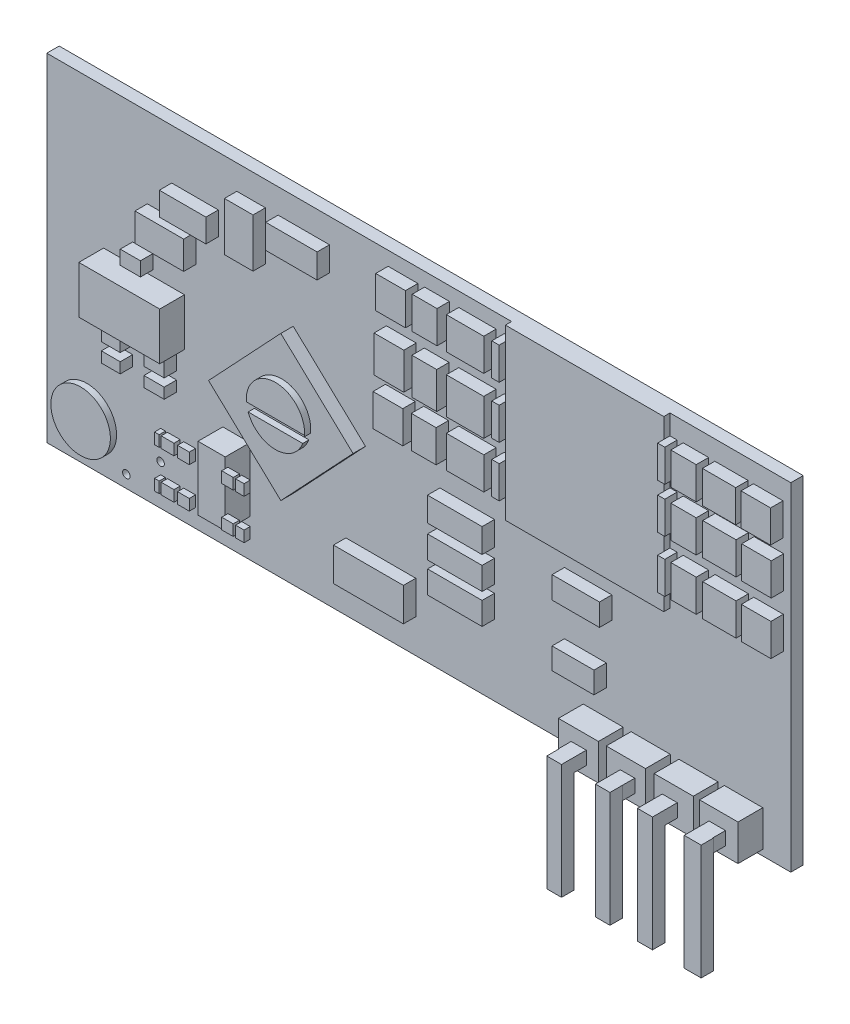
SolidWorks part; units mm, degrees
ref_plane "Front Plane" through (0, 0, 0) normal (0, 0, 1) x (1, 0, 0)
ref_plane "Top Plane" through (0, 0, 0) normal (0, 1, 0) x (1, 0, 0)
ref_plane "Right Plane" through (0, 0, 0) normal (1, 0, 0) x (0, 0, -1)
sketch "Sketch2" plane through (0, 0, 0) normal (0, 0, 1) x (1, 0, 0)
  line L1 (-9.0054, 3.5685) -> (20.9946, 3.5685)
  line L2 (-9.0054, 3.5685) -> (-9.0054, -10.0315)
  line L3 (-9.0054, -10.0315) -> (20.9946, -10.0315)
  line L4 (20.9946, 3.5685) -> (20.9946, -10.0315)
  dimension "D1" = 13.6
  dimension "D2" = 30
extrude "Boss-Extrude1" add sketch "Sketch2" along normal blind 0.5 contours L2 L1 L4 L3
sketch "Sketch3" plane through (0, 0, 0.5) normal (0, 0, 1) x (1, 0, 0)
  line L0 (-9.0054, 3.5685) -> (20.9946, 3.5685) construction
  line L1 (9.736, 3.5685) -> (16.1221, 3.5685)
  line L2 (9.736, 3.5685) -> (9.736, -3.2477)
  line L3 (9.736, -3.2477) -> (16.1221, -3.2477)
  line L4 (16.1221, 3.5685) -> (16.1221, -3.2477)
extrude "Boss-Extrude2" add sketch "Sketch3" along normal blind 0.25
sketch "Sketch4" plane through (0, 0, 0.5) normal (0, 0, 1) x (1, 0, 0)
  line L0 (16.1221, -3.2477) -> (16.1221, 3.5685) construction
  line L1 (16.1221, 2.7685) -> (16.4124, 2.7685)
  line L2 (16.1221, 2.7685) -> (16.1221, 1.4685)
  line L3 (16.1221, 1.4685) -> (16.4124, 1.4685)
  line L4 (16.4124, 2.7685) -> (16.4124, 1.4685)
  line L5 (16.1221, -3.2477) -> (16.1221, 3.5685) construction
  line L6 (16.6559, 2.7933) -> (17.6802, 2.7933)
  line L7 (16.6559, 2.7933) -> (16.6559, 1.4933)
  line L8 (16.6559, 1.4933) -> (17.6802, 1.4933)
  line L9 (17.6802, 2.7933) -> (17.6802, 1.4933)
  line L10 (17.9298, 2.787) -> (19.2737, 2.787)
  line L11 (17.9298, 2.787) -> (17.9298, 1.487)
  line L12 (17.9298, 1.487) -> (19.2737, 1.487)
  line L13 (19.2737, 2.787) -> (19.2737, 1.487)
  line L14 (19.4867, 2.7799) -> (20.6781, 2.7799)
  line L15 (19.4867, 2.7799) -> (19.4867, 1.4799)
  line L16 (19.4867, 1.4799) -> (20.6781, 1.4799)
  line L17 (20.6781, 2.7799) -> (20.6781, 1.4799)
  line L18 (16.1221, 0.9523) -> (16.4124, 0.9523)
  line L19 (16.1221, 0.9523) -> (16.1221, -0.3477)
  line L20 (16.1221, -0.3477) -> (16.4124, -0.3477)
  line L21 (16.4124, 0.9523) -> (16.4124, -0.3477)
  line L22 (9.736, 3.5685) -> (9.736, -3.2477) construction
  line L23 (17.9431, 0.9721) -> (19.287, 0.9721)
  line L24 (17.9431, 0.9721) -> (17.9431, -0.3279)
  line L25 (16.6559, 0.9361) -> (17.6802, 0.9361)
  line L26 (16.6559, 0.9361) -> (16.6559, -0.3639)
  line L27 (16.6559, -0.3639) -> (17.6802, -0.3639)
  line L28 (17.6802, 0.9361) -> (17.6802, -0.3639)
  line L29 (17.9431, -0.3279) -> (19.287, -0.3279)
  line L30 (19.287, 0.9721) -> (19.287, -0.3279)
  line L31 (19.5134, 0.9454) -> (20.7048, 0.9454)
  line L32 (19.5134, 0.9454) -> (19.5134, -0.3546)
  line L33 (19.5134, -0.3546) -> (20.7048, -0.3546)
  line L34 (20.7048, 0.9454) -> (20.7048, -0.3546)
  line L35 (16.1221, -1.1477) -> (16.4124, -1.1477)
  line L36 (16.1221, -1.1477) -> (16.1221, -2.4477)
  line L37 (16.1221, -2.4477) -> (16.4124, -2.4477)
  line L38 (16.4124, -1.1477) -> (16.4124, -2.4477)
  line L39 (16.6559, -1.1358) -> (17.6802, -1.1358)
  line L40 (16.6559, -1.1358) -> (16.6559, -2.4358)
  line L41 (16.6559, -2.4358) -> (17.6802, -2.4358)
  line L42 (17.6802, -1.1358) -> (17.6802, -2.4358)
  line L43 (17.9431, -1.1625) -> (19.287, -1.1625)
  line L44 (17.9431, -1.1625) -> (17.9431, -2.4625)
  line L45 (17.9431, -2.4625) -> (19.287, -2.4625)
  line L46 (19.287, -1.1625) -> (19.287, -2.4625)
  line L47 (19.5, -1.1759) -> (20.6914, -1.1759)
  line L48 (19.5, -1.1759) -> (19.5, -2.4759)
  line L49 (19.5, -2.4759) -> (20.6914, -2.4759)
  line L50 (20.6914, -1.1759) -> (20.6914, -2.4759)
  line L51 (9.736, -2.4477) -> (9.436, -2.4477)
  line L52 (9.736, -2.4477) -> (9.736, -1.1477)
  line L53 (9.736, -1.1477) -> (9.436, -1.1477)
  line L54 (9.436, -2.4477) -> (9.436, -1.1477)
  line L56 (9.736, -0.406) -> (9.436, -0.406)
  line L57 (9.736, -0.406) -> (9.736, 0.894)
  line L58 (9.736, 0.894) -> (9.436, 0.894)
  line L59 (9.436, -0.406) -> (9.436, 0.894)
  line L60 (9.736, 1.694) -> (9.436, 1.694)
  line L61 (9.736, 1.694) -> (9.736, 2.994)
  line L62 (9.736, 2.994) -> (9.436, 2.994)
  line L63 (9.436, 1.694) -> (9.436, 2.994)
  line L64 (9.1141, 2.994) -> (7.6057, 2.994)
  line L65 (9.1141, 2.994) -> (9.1141, 1.694)
  line L66 (9.1141, 1.694) -> (7.6057, 1.694)
  line L67 (7.6057, 2.994) -> (7.6057, 1.694)
  line L68 (7.6057, 0.894) -> (9.1141, 0.894)
  line L69 (7.6057, 0.894) -> (7.6057, -0.5749)
  line L70 (7.6057, -0.5749) -> (9.1141, -0.5749)
  line L71 (9.1141, 0.894) -> (9.1141, -0.5749)
  line L72 (9.1141, -1.1477) -> (7.6057, -1.1477)
  line L73 (9.1141, -1.1477) -> (9.1141, -2.4477)
  line L74 (9.1141, -2.4477) -> (7.6057, -2.4477)
  line L75 (7.6057, -1.1477) -> (7.6057, -2.4477)
  line L76 (7.2285, 3.0173) -> (6.2285, 3.0173)
  line L77 (7.2285, 3.0173) -> (7.2285, 1.7173)
  line L78 (7.2285, 1.7173) -> (6.2285, 1.7173)
  line L79 (6.2285, 3.0173) -> (6.2285, 1.7173)
  line L80 (7.2169, 0.8823) -> (6.2169, 0.8823)
  line L81 (7.2169, 0.8823) -> (7.2169, -0.5865)
  line L82 (7.2169, -0.5865) -> (6.2169, -0.5865)
  line L83 (6.2169, 0.8823) -> (6.2169, -0.5865)
  line L84 (7.1936, -1.1593) -> (6.1936, -1.1593)
  line L85 (7.1936, -1.1593) -> (7.1936, -2.4593)
  line L86 (7.1936, -2.4593) -> (6.1936, -2.4593)
  line L87 (6.1936, -1.1593) -> (6.1936, -2.4593)
  line L88 (5.9576, 3.0078) -> (4.7576, 3.0078)
  line L89 (5.9576, 3.0078) -> (5.9576, 1.7078)
  line L90 (5.9576, 1.7078) -> (4.7576, 1.7078)
  line L91 (4.7576, 3.0078) -> (4.7576, 1.7078)
  line L92 (5.8903, 0.8951) -> (4.6903, 0.8951)
  line L93 (5.8903, 0.8951) -> (5.8903, -0.5737)
  line L94 (5.8903, -0.5737) -> (4.6903, -0.5737)
  line L95 (4.6903, 0.8951) -> (4.6903, -0.5737)
  line L96 (5.8494, -1.1678) -> (4.6494, -1.1678)
  line L97 (5.8494, -1.1678) -> (5.8494, -2.4678)
  line L98 (5.8494, -2.4678) -> (4.6494, -2.4678)
  line L99 (4.6494, -1.1678) -> (4.6494, -2.4678)
  dimension "D1" = 1.3
  dimension "D2" = 1.3
  dimension "D3" = 1.3
  dimension "D4" = 1.3
  dimension "D5" = 1.3
  dimension "D6" = 1.3
  dimension "D7" = 1.3
  dimension "D8" = 1.3
  dimension "D9" = 1.3
  dimension "D10" = 1.3
  dimension "D11" = 1.3
  dimension "D12" = 1.3
  dimension "D13" = 0.8
  dimension "D14" = 0.8
  dimension "D15" = 0.8
  dimension "D16" = 1.3
  dimension "D17" = 1.3
  dimension "D18" = 1.3
  dimension "D19" = 0.8
  dimension "D20" = 0.8
  dimension "D21" = 0.8
  dimension "D22" = 0.2903
  dimension "D23" = 0.3
  dimension "D24" = 0.3
  dimension "D25" = 0.3
  dimension "D26" = 1.0243
  dimension "D27" = 1
  dimension "D28" = 1
  dimension "D29" = 1
  dimension "D30" = 1.4688
  dimension "D31" = 1.1914
  dimension "D32" = 1.2
  dimension "D33" = 1.2
  dimension "D34" = 1.2
extrude "Boss-Extrude8" add sketch "Sketch4" along normal blind 0.5
sketch "Sketch5" plane through (0, 0, 0.5) normal (0, 0, 1) x (1, 0, 0)
  line L1 (6.8465, -3.6881) -> (9.0462, -3.6881)
  line L2 (6.8465, -3.6881) -> (6.8465, -4.6657)
  line L3 (6.8465, -4.6657) -> (9.0462, -4.6657)
  line L4 (9.0462, -3.6881) -> (9.0462, -4.6657)
  line L5 (6.8465, -5.0435) -> (9.0462, -5.0435)
  line L6 (6.8465, -5.0435) -> (6.8465, -5.9544)
  line L7 (6.8465, -5.9544) -> (9.0462, -5.9544)
  line L8 (9.0462, -5.0435) -> (9.0462, -5.9544)
  line L9 (6.8465, -6.2655) -> (9.0462, -6.2655)
  line L10 (6.8465, -6.2655) -> (6.8465, -7.1765)
  line L11 (6.8465, -7.1765) -> (9.0462, -7.1765)
  line L12 (9.0462, -6.2655) -> (9.0462, -7.1765)
  line L13 (11.868, -3.9547) -> (13.7789, -3.9547)
  line L14 (11.868, -3.9547) -> (11.868, -4.8435)
  line L15 (11.868, -4.8435) -> (13.7789, -4.8435)
  line L16 (13.7789, -3.9547) -> (13.7789, -4.8435)
  line L17 (11.868, -6.4433) -> (13.5567, -6.4433)
  line L18 (11.868, -6.4433) -> (11.868, -7.3098)
  line L19 (11.868, -7.3098) -> (13.5567, -7.3098)
  line L20 (13.5567, -6.4433) -> (13.5567, -7.3098)
extrude "Boss-Extrude9" add sketch "Sketch5" along normal blind 0.5
sketch "Sketch6" plane through (0, 0, 0.5) normal (0, 0, 1) x (1, 0, 0)
  line L1 (12.625, -8.3439) -> (14.2373, -8.3439)
  line L2 (12.625, -8.3439) -> (12.625, -9.7981)
  line L3 (12.625, -9.7981) -> (14.2373, -9.7981)
  line L4 (14.2373, -8.3439) -> (14.2373, -9.7981)
  line L5 (14.5534, -8.3439) -> (16.1341, -8.3439)
  line L6 (14.5534, -8.3439) -> (14.5534, -9.7981)
  line L7 (14.5534, -9.7981) -> (16.1341, -9.7981)
  line L8 (16.1341, -8.3439) -> (16.1341, -9.7981)
  line L9 (16.4818, -8.3439) -> (18.0625, -8.3439)
  line L10 (16.4818, -8.3439) -> (16.4818, -9.7981)
  line L11 (16.4818, -9.7981) -> (18.0625, -9.7981)
  line L12 (18.0625, -8.3439) -> (18.0625, -9.7981)
  line L13 (18.3154, -8.3439) -> (19.8645, -8.3439)
  line L14 (18.3154, -8.3439) -> (18.3154, -9.7981)
  line L15 (18.3154, -9.7981) -> (19.8645, -9.7981)
  line L16 (19.8645, -8.3439) -> (19.8645, -9.7981)
extrude "Boss-Extrude11" add sketch "Sketch6" along normal blind 1
sketch "Sketch7" plane through (0, 0, 1.5) normal (0, 0, 1) x (1, 0, 0)
  line L1 (13.1379, -8.8933) -> (13.7485, -8.8933)
  line L2 (13.1379, -8.8933) -> (13.1379, -9.4308)
  line L3 (13.1379, -9.4308) -> (13.7485, -9.4308)
  line L4 (13.7485, -8.8933) -> (13.7485, -9.4308)
  line L5 (15.1169, -8.8933) -> (15.7036, -8.8933)
  line L6 (15.1169, -8.8933) -> (15.1169, -9.4308)
  line L7 (15.1169, -9.4308) -> (15.7036, -9.4308)
  line L8 (15.7036, -8.8933) -> (15.7036, -9.4308)
  line L9 (16.8122, -8.8933) -> (17.4173, -8.8933)
  line L10 (16.8122, -8.8933) -> (16.8122, -9.4308)
  line L11 (16.8122, -9.4308) -> (17.4173, -9.4308)
  line L12 (17.4173, -8.8933) -> (17.4173, -9.4308)
  line L13 (18.6964, -8.8933) -> (19.3604, -8.8933)
  line L14 (18.6964, -8.8933) -> (18.6964, -9.4308)
  line L15 (18.6964, -9.4308) -> (19.3604, -9.4308)
  line L16 (19.3604, -8.8933) -> (19.3604, -9.4308)
extrude "Boss-Extrude12" add sketch "Sketch7" along normal blind 0.5
sketch "Sketch8" plane through (0, 0, 2) normal (0, 0, 1) x (1, 0, 0)
  line L0 (13.7485, -8.8933) -> (13.1379, -8.8933) construction
  line L1 (13.1548, -8.8933) -> (13.7485, -8.8933)
  line L2 (13.1548, -8.8933) -> (13.1548, -13.5335)
  line L3 (13.1548, -13.5335) -> (13.7485, -13.5335)
  line L4 (13.7485, -8.8933) -> (13.7485, -13.5335)
  line L5 (18.6964, -8.8933) -> (18.6964, -9.4308) construction
  line L6 (15.1169, -8.8933) -> (15.7029, -8.8933)
  line L7 (15.1169, -8.8933) -> (15.1169, -13.5335)
  line L8 (15.1169, -13.5335) -> (15.7029, -13.5335)
  line L9 (15.7029, -8.8933) -> (15.7029, -13.5335)
  line L10 (16.8122, -8.8933) -> (17.4173, -8.8933)
  line L11 (16.8122, -8.8933) -> (16.8122, -13.5335)
  line L12 (16.8122, -13.5335) -> (17.4173, -13.5335)
  line L13 (17.4173, -8.8933) -> (17.4173, -13.5335)
  line L14 (18.6964, -8.8933) -> (19.3797, -8.8933)
  line L15 (18.6964, -8.8933) -> (18.6964, -13.5335)
  line L16 (18.6964, -13.5335) -> (19.3797, -13.5335)
  line L17 (19.3797, -8.8933) -> (19.3797, -13.5335)
extrude "Boss-Extrude13" add sketch "Sketch8" along normal blind 0.5
sketch "Sketch9" plane through (0, 0, 0.5) normal (0, 0, 1) x (1, 0, 0)
  line L0 (0.9308, -0.9992) -> (-1.9824, -4.1004)
  line L1 (0.9308, -0.9992) -> (3.8441, -3.7359)
  line L2 (-1.9824, -4.1004) -> (0.9308, -6.8371)
  line L3 (3.8441, -3.7359) -> (0.9308, -6.8371)
extrude "Boss-Extrude14" add sketch "Sketch9" along normal blind 0.5
sketch "Sketch10" plane through (0, 0, 1) normal (0, 0, 1) x (1, 0, 0)
  circle A0 centre (0.9631, -3.7408) radius 1.174
extrude "Boss-Extrude16" add sketch "Sketch10" along normal blind 0.25
sketch "Sketch12" plane through (0, 0, 1.25) normal (0, 0, 1) x (1, 0, 0)
  line L1 (-0.2073, -3.8339) -> (2.128, -3.8339)
  line L2 (-0.2073, -3.8339) -> (-0.2073, -4.1503)
  line L3 (-0.2073, -4.1503) -> (2.128, -4.1503)
  line L4 (2.128, -3.8339) -> (2.128, -4.1503)
  circle A0 centre (0.9631, -3.7408) radius 1.174 construction
extrude "Cut-Extrude6" cut sketch "Sketch12" against normal blind 0.25 contours L2 L1 L4 L3
sketch "Sketch13" plane through (0, 0, 0.5) normal (0, 0, 1) x (1, 0, 0)
  circle A0 centre (-7.3905, -8.353) radius 1.2
  dimension "D1" = 2.4
extrude "Boss-Extrude17" add sketch "Sketch13" along normal blind 0.25
sketch "Sketch14" plane through (0, 0, 0.5) normal (0, 0, 1) x (1, 0, 0)
  line L1 (-1.9075, -5.934) -> (-0.8109, -5.934)
  line L2 (-1.9075, -5.934) -> (-1.9075, -8.5143)
  line L3 (-1.9075, -8.5143) -> (-0.8109, -8.5143)
  line L4 (-0.8109, -5.934) -> (-0.8109, -8.5143)
extrude "Boss-Extrude19" add sketch "Sketch14" along normal blind 1
sketch "Sketch15" plane through (0, 0, 1.5) normal (0, 0, 1) x (1, 0, 0)
  line L1 (-2.0102, -6.2379) -> (-2.4824, -6.2379)
  line L2 (-2.0102, -6.2379) -> (-2.0102, -6.6811)
  line L3 (-2.0102, -6.6811) -> (-2.4824, -6.6811)
  line L4 (-2.4824, -6.2379) -> (-2.4824, -6.6811)
  line L5 (-2.6277, -6.2379) -> (-3.1435, -6.2379)
  line L6 (-2.6277, -6.2379) -> (-2.6277, -6.6811)
  line L7 (-2.6277, -6.6811) -> (-3.1435, -6.6811)
  line L8 (-3.1435, -6.2379) -> (-3.1435, -6.6811)
  line L9 (-3.4123, -6.2379) -> (-3.2234, -6.2379)
  line L10 (-3.4123, -6.2379) -> (-3.4123, -6.6811)
  line L11 (-3.4123, -6.6811) -> (-3.2234, -6.6811)
  line L12 (-3.2234, -6.2379) -> (-3.2234, -6.6811)
  line L13 (-2.0102, -8.301) -> (-2.4824, -8.301)
  line L14 (-2.0102, -8.301) -> (-2.0102, -7.8579)
  line L15 (-2.0102, -7.8579) -> (-2.4824, -7.8579)
  line L16 (-2.4824, -8.301) -> (-2.4824, -7.8579)
  line L17 (-2.6277, -7.8579) -> (-3.1435, -7.8579)
  line L18 (-2.6277, -7.8579) -> (-2.6277, -8.301)
  line L19 (-2.6277, -8.301) -> (-3.1435, -8.301)
  line L20 (-3.1435, -7.8579) -> (-3.1435, -8.301)
  line L21 (-3.2234, -7.8579) -> (-3.4123, -7.8579)
  line L22 (-3.2234, -7.8579) -> (-3.2234, -8.301)
  line L23 (-3.2234, -8.301) -> (-3.4123, -8.301)
  line L24 (-3.4123, -7.8579) -> (-3.4123, -8.301)
  line L25 (-0.7026, -6.2379) -> (-0.2377, -6.2379)
  line L26 (-0.7026, -6.2379) -> (-0.7026, -6.6811)
  line L27 (-0.7026, -6.6811) -> (-0.2377, -6.6811)
  line L28 (-0.2377, -6.2379) -> (-0.2377, -6.6811)
  line L29 (-0.1433, -6.2379) -> (0.1982, -6.2379)
  line L30 (-0.1433, -6.2379) -> (-0.1433, -6.6811)
  line L31 (-0.1433, -6.6811) -> (0.1982, -6.6811)
  line L32 (0.1982, -6.2379) -> (0.1982, -6.6811)
  line L33 (-0.7026, -7.8579) -> (-0.2377, -7.8579)
  line L34 (-0.7026, -7.8579) -> (-0.7026, -8.301)
  line L35 (-0.7026, -8.301) -> (-0.2377, -8.301)
  line L36 (-0.2377, -7.8579) -> (-0.2377, -8.301)
  line L37 (-0.1433, -7.8579) -> (0.1982, -7.8579)
  line L38 (-0.1433, -7.8579) -> (-0.1433, -8.301)
  line L39 (-0.1433, -8.301) -> (0.1982, -8.301)
  line L40 (0.1982, -7.8579) -> (0.1982, -8.301)
extrude "Boss-Extrude20" add sketch "Sketch15" along normal blind 0.25 separate body
sketch "Sketch16" plane through (0, 0, 0.5) normal (0, 0, 1) x (1, 0, 0)
  circle A0 centre (-5.7988, -9.5294) radius 0.15
  circle A1 centre (-4.4159, -8.4091) radius 0.15
  dimension "D1" = 0.3
  dimension "D2" = 0.3
extrude "Cut-Extrude7" cut sketch "Sketch16" against normal blind 4.25
sketch "Sketch17" plane through (0, 0, 0.5) normal (0, 0, 1) x (1, 0, 0)
  line L1 (-6.2949, -1.9058) -> (-2.8154, -1.9058)
  line L2 (-6.2949, -1.9058) -> (-6.2949, -3.5495)
  line L3 (-6.2949, -3.5495) -> (-2.8154, -3.5495)
  line L4 (-2.8154, -1.9058) -> (-2.8154, -3.5495)
  line L5 (-4.9501, -0.7958) -> (-2.9862, -0.7958)
  line L6 (-4.9501, -0.7958) -> (-4.9501, 0.3355)
  line L7 (-4.9501, 0.3355) -> (-2.9862, 0.3355)
  line L8 (-2.9862, -0.7958) -> (-2.9862, 0.3355)
  line L9 (-3.9681, 1.5523) -> (-2.0896, 1.5523)
  line L10 (-3.9681, 1.5523) -> (-3.9681, 0.613)
  line L11 (-3.9681, 0.613) -> (-2.0896, 0.613)
  line L12 (-2.0896, 1.5523) -> (-2.0896, 0.613)
  line L13 (-1.3425, 2.5769) -> (-0.1898, 2.5769)
  line L14 (-1.3425, 2.5769) -> (-1.3425, 0.613)
  line L15 (-1.3425, 0.613) -> (-0.1898, 0.613)
  line L16 (-0.1898, 2.5769) -> (-0.1898, 0.613)
  line L17 (0.3225, 2.5769) -> (2.3931, 2.5769)
  line L18 (0.3225, 2.5769) -> (0.3225, 1.595)
  line L19 (0.3225, 1.595) -> (2.3931, 1.595)
  line L20 (2.3931, 2.5769) -> (2.3931, 1.595)
  line L21 (3.0548, -7.3278) -> (5.8726, -7.3278)
  line L22 (3.0548, -7.3278) -> (3.0548, -8.6726)
  line L23 (3.0548, -8.6726) -> (5.8726, -8.6726)
  line L24 (5.8726, -7.3278) -> (5.8726, -8.6726)
  line L25 (-5.8039, -3.7203) -> (-5.5051, -3.7203)
  line L26 (-5.8039, -3.7203) -> (-5.8039, -4.6595)
  line L27 (-5.8039, -4.6595) -> (-5.5051, -4.6595)
  line L28 (-5.5051, -3.7203) -> (-5.5051, -4.6595)
  line L29 (-3.6906, -3.7203) -> (-3.4131, -3.7203)
  line L30 (-3.6906, -3.7203) -> (-3.6906, -4.6595)
  line L31 (-3.6906, -4.6595) -> (-3.4131, -4.6595)
  line L32 (-3.4131, -3.7203) -> (-3.4131, -4.6595)
  line L33 (-4.9501, -1.9058) -> (-4.5551, -1.9058)
  line L34 (-4.9501, -1.9058) -> (-4.9501, -1.0306)
  line L35 (-4.9501, -1.0306) -> (-4.5551, -1.0306)
  line L36 (-4.5551, -1.9058) -> (-4.5551, -1.0306)
extrude "Boss-Extrude22" add sketch "Sketch17" along normal blind 0.5 contours L5 L8 L7 L6 | L12 L9 L10 L11 | L16 L13 L14 L15 | L20 L17 L18 L19 | L24 L21 L22 L23
sketch "Sketch19" plane through (0, 0, 0.5) normal (0, 0, 1) x (1, 0, 0)
  line L1 (-6.7136, -2.091) -> (-3.4536, -2.091)
  line L2 (-6.7136, -2.091) -> (-6.7136, -4.0045)
  line L3 (-6.7136, -4.0045) -> (-3.4536, -4.0045)
  line L4 (-3.4536, -2.091) -> (-3.4536, -4.0045)
  line L5 (-6.2884, -4.2702) -> (-5.4556, -4.2702)
  line L6 (-6.2884, -4.2702) -> (-6.2884, -4.9612)
  line L7 (-6.2884, -4.9612) -> (-5.4556, -4.9612)
  line L8 (-5.4556, -4.2702) -> (-5.4556, -4.9612)
  line L9 (-6.2884, -5.3687) -> (-5.4556, -5.3687)
  line L10 (-6.2884, -5.3687) -> (-6.2884, -5.8648)
  line L11 (-6.2884, -5.8648) -> (-5.4556, -5.8648)
  line L12 (-5.4556, -5.3687) -> (-5.4556, -5.8648)
  line L13 (-4.7292, -4.2702) -> (-3.8433, -4.2702)
  line L14 (-4.7292, -4.2702) -> (-4.7292, -4.9612)
  line L15 (-4.7292, -4.9612) -> (-3.8433, -4.9612)
  line L16 (-3.8433, -4.2702) -> (-3.8433, -4.9612)
  line L17 (-4.7292, -5.3687) -> (-3.8433, -5.3687)
  line L18 (-4.7292, -5.3687) -> (-4.7292, -5.8648)
  line L19 (-4.7292, -5.8648) -> (-3.8433, -5.8648)
  line L20 (-3.8433, -5.3687) -> (-3.8433, -5.8648)
  line L21 (-5.4556, -1.8252) -> (-4.7292, -1.8252)
  line L22 (-5.4556, -1.8252) -> (-5.4556, -1.2582)
  line L23 (-5.4556, -1.2582) -> (-4.7292, -1.2582)
  line L24 (-4.7292, -1.8252) -> (-4.7292, -1.2582)
extrude "Boss-Extrude26" add sketch "Sketch19" along normal blind 1 contours L2 L1 L4 L3
sketch "Sketch22" plane through (0, 0, 0.5) normal (0, 0, 1) x (1, 0, 0)
  line L1 (-6.3061, -4.1816) -> (-5.5442, -4.1816)
  line L2 (-6.3061, -4.1816) -> (-6.3061, -4.9081)
  line L3 (-6.3061, -4.9081) -> (-5.5442, -4.9081)
  line L4 (-5.5442, -4.1816) -> (-5.5442, -4.9081)
  line L5 (-6.3061, -5.227) -> (-5.5442, -5.227)
  line L6 (-6.3061, -5.227) -> (-6.3061, -5.6522)
  line L7 (-6.3061, -5.6522) -> (-5.5442, -5.6522)
  line L8 (-5.5442, -5.227) -> (-5.5442, -5.6522)
  line L9 (-4.5875, -4.1816) -> (-3.7725, -4.1816)
  line L10 (-4.5875, -4.1816) -> (-4.5875, -4.9081)
  line L11 (-4.5875, -4.9081) -> (-3.7725, -4.9081)
  line L12 (-3.7725, -4.1816) -> (-3.7725, -4.9081)
  line L13 (-4.5875, -5.227) -> (-3.7725, -5.227)
  line L14 (-4.5875, -5.227) -> (-4.5875, -5.6522)
  line L15 (-4.5875, -5.6522) -> (-3.7725, -5.6522)
  line L16 (-3.7725, -5.227) -> (-3.7725, -5.6522)
  line L17 (-5.5442, -1.8606) -> (-4.7292, -1.8606)
  line L18 (-5.5442, -1.8606) -> (-5.5442, -1.2937)
  line L19 (-5.5442, -1.2937) -> (-4.7292, -1.2937)
  line L20 (-4.7292, -1.8606) -> (-4.7292, -1.2937)
extrude "Boss-Extrude27" add sketch "Sketch22" along normal blind 0.5 separate body
